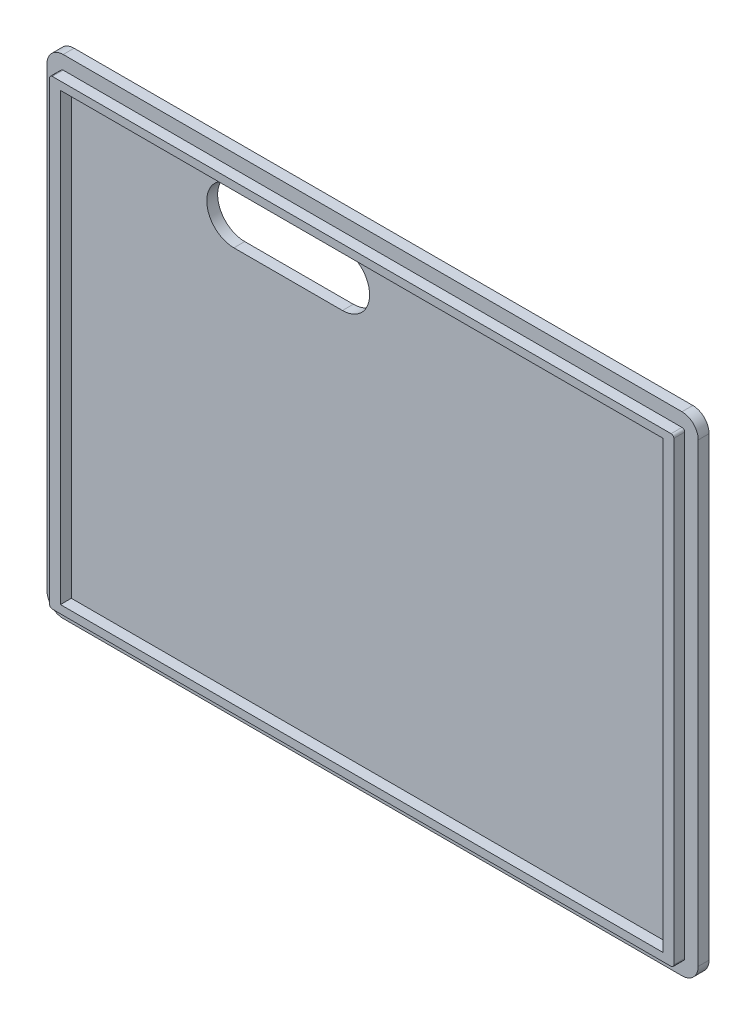
SolidWorks part; units mm, degrees
ref_plane "Plan de face" through (0, 0, 0) normal (0, 0, 1) x (1, 0, 0)
ref_plane "Plan de dessus" through (0, 0, 0) normal (0, 1, 0) x (1, 0, 0)
ref_plane "Plan de droite" through (0, 0, 0) normal (1, 0, 0) x (0, 0, -1)
sketch "Esquisse1" plane through (0, 0, 0) normal (0, 0, 1) x (1, 0, 0)
  line L1 (60, -45) -> (-60, -45)
  line L2 (60, -45) -> (60, 45)
  line L3 (60, 45) -> (-60, 45)
  line L4 (-60, -45) -> (-60, 45)
  line L5 (60, -45) -> (-60, 45) construction
  line L6 (60, 45) -> (-60, -45) construction
  point P0 (0, 0)
  dimension "D1" = 120
  dimension "D2" = 90
extrude "Boss.-Extru.1" add sketch "Esquisse1" along normal blind 2
sketch "Esquisse2" plane through (0, 0, 2) normal (0, 0, 1) x (1, 0, 0)
  line L1 (57.5, -42.5) -> (-57.5, -42.5)
  line L2 (57.5, -42.5) -> (57.5, 42.5)
  line L3 (57.5, 42.5) -> (-57.5, 42.5)
  line L4 (-57.5, -42.5) -> (-57.5, 42.5)
  line L5 (57.5, -42.5) -> (-57.5, 42.5) construction
  line L6 (57.5, 42.5) -> (-57.5, -42.5) construction
  line L7 (55.5, -41.0217) -> (-55.5, -41.0217)
  line L8 (55.5, -41.0217) -> (55.5, 41.0217)
  line L9 (55.5, 41.0217) -> (-55.5, 41.0217)
  line L10 (-55.5, -41.0217) -> (-55.5, 41.0217)
  line L11 (55.5, -41.0217) -> (-55.5, 41.0217) construction
  line L12 (55.5, 41.0217) -> (-55.5, -41.0217) construction
  point P0 (0, 0)
  point P6 (0, 0)
  dimension "D1" = 115
  dimension "D2" = 85
  dimension "D3" = 2
extrude "Boss.-Extru.2" add sketch "Esquisse2" along normal blind 2
sketch "Esquisse3" plane through (0, 0, 0) normal (0, 0, -1) x (-1, 0, 0)
  line L0 (5.5484, 34.875) -> (25.5484, 34.875) construction
  line L1 (5.5484, 39.875) -> (25.5484, 39.875)
  line L2 (5.5484, 29.875) -> (25.5484, 29.875)
  arc A0 (5.5484, 39.875) -> (5.5484, 29.875) centre (5.5484, 34.875) ccw
  arc A1 (25.5484, 29.875) -> (25.5484, 39.875) centre (25.5484, 34.875) ccw
  point P2 (15.5484, 34.875)
  dimension "D1" = 20
  dimension "D2" = 10
extrude "Enlèv. mat.-Extru.1" cut sketch "Esquisse3" against normal blind 2
fillet "Congé1" radius 3 4 edges at (60, 45, 1) (-60, -45, 1) (-60, 45, 1) (60, -45, 1)
fillet "Congé2" radius 0.5 4 edges at (57.5, -42.5, 3) (57.5, 42.5, 3) (-57.5, 42.5, 3) (-57.5, -42.5, 3)
